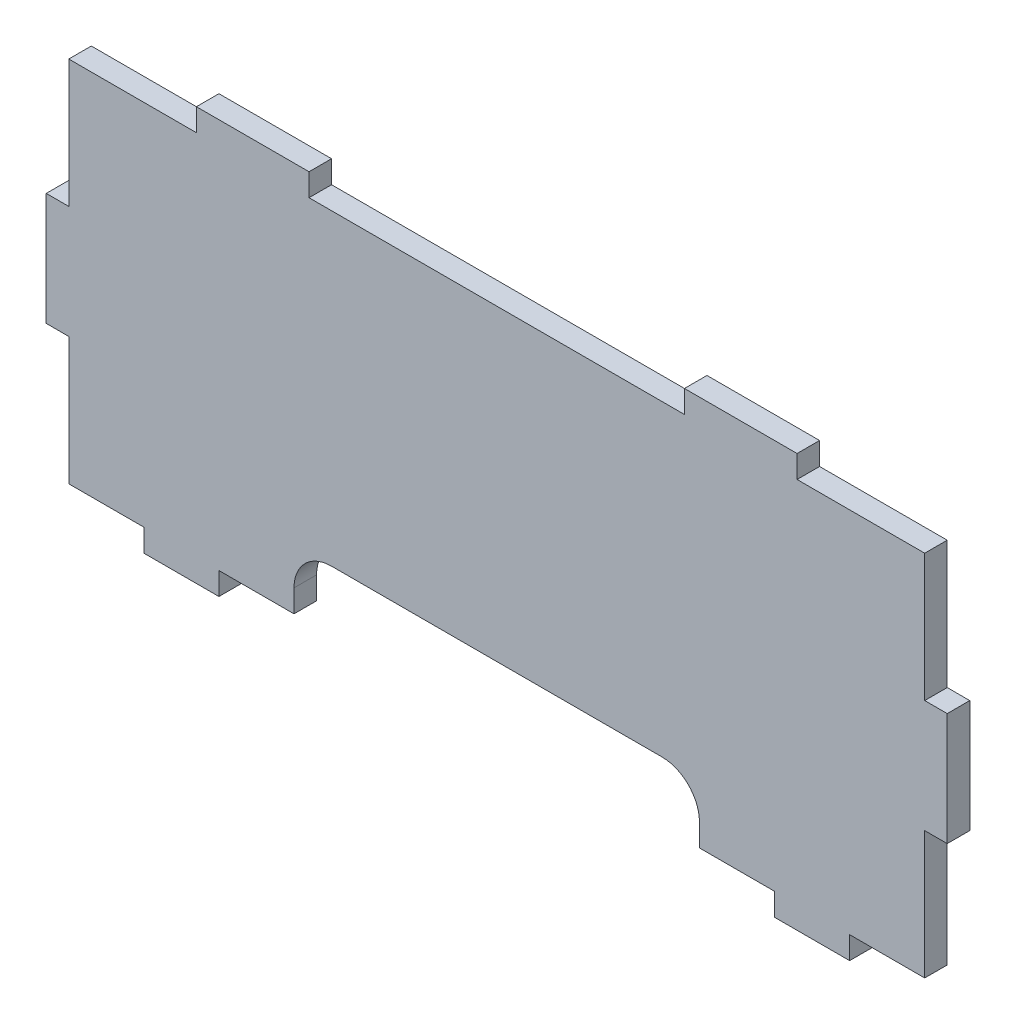
SolidWorks part; units mm, degrees
material "ABS PC"
ref_plane "Front Plane" through (0, 0, 0) normal (0, 0, 1) x (1, 0, 0)
ref_plane "Top Plane" through (0, 0, 0) normal (0, 1, 0) x (1, 0, 0)
ref_plane "Right Plane" through (0, 0, 0) normal (1, 0, 0) x (0, 0, -1)
sketch "Sketch1" plane through (0, 0, 0) normal (0, 0, 1) x (1, 0, 0)
  line L0 (-57, -28.5) -> (-57, -11.5)
  line L1 (-57, 20.5) -> (-40, 20.5)
  line L2 (57, 20.5) -> (57, 3.5)
  line L3 (-40, 20.5) -> (-40, 23.5)
  line L4 (-40, 23.5) -> (-25, 23.5)
  line L5 (-25, 23.5) -> (-25, 20.5)
  line L6 (25, 20.5) -> (25, 23.5)
  line L7 (25, 23.5) -> (40, 23.5)
  line L8 (40, 23.5) -> (40, 20.5)
  line L9 (-25, 20.5) -> (25, 20.5)
  line L10 (40, 20.5) -> (57, 20.5)
  line L11 (-57, -28.5) -> (-47, -28.5)
  line L12 (-27, -28.5) -> (-27, -25.5)
  line L13 (-22, -20.5) -> (22, -20.5)
  line L14 (27, -25.5) -> (27, -28.5)
  line L15 (27, -28.5) -> (37, -28.5)
  line L16 (0, 20.5) -> (0, 0) construction
  line L17 (0, 0) -> (0, -20.5) construction
  line L18 (-57, 3.5) -> (-60, 3.5)
  line L19 (-60, 3.5) -> (-60, -11.5)
  line L20 (-60, -11.5) -> (-57, -11.5)
  line L21 (57, 3.5) -> (60, 3.5)
  line L22 (60, 3.5) -> (60, -11.5)
  line L23 (60, -11.5) -> (57, -11.5)
  line L24 (-57, 3.5) -> (-57, 20.5)
  line L25 (57, -11.5) -> (57, -28.5)
  line L26 (-47, -28.5) -> (-47, -31.5)
  line L27 (-47, -31.5) -> (-37, -31.5)
  line L28 (-37, -31.5) -> (-37, -28.5)
  line L29 (37, -28.5) -> (37, -31.5)
  line L30 (37, -31.5) -> (47, -31.5)
  line L31 (47, -31.5) -> (47, -28.5)
  line L32 (-37, -28.5) -> (-27, -28.5)
  line L33 (47, -28.5) -> (57, -28.5)
  arc A0 (27, -25.5) -> (22, -20.5) centre (22, -25.5) ccw
  arc A1 (-22, -20.5) -> (-27, -25.5) centre (-22, -25.5) ccw
  dimension "D1" = 5
  dimension "D2" = 15
  dimension "D3" = 50
  dimension "D4" = 114
  dimension "D5" = 3
  dimension "D6" = 55
  dimension "D7" = 8
  dimension "D8" = 30
  dimension "D9" = 20
  dimension "D10" = 10
extrude "Boss-Extrude1" add sketch "Sketch1" along normal blind 3
